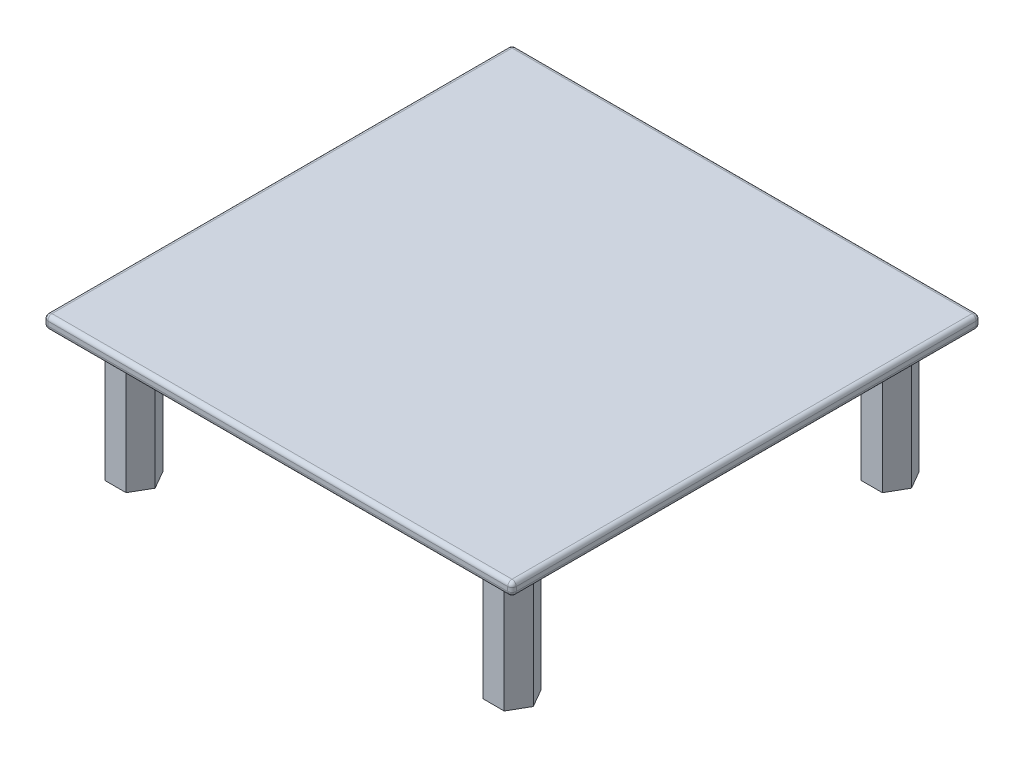
SolidWorks part; units mm, degrees
material "6061-T6 (SS)"
ref_plane "Front Plane" through (0, 0, 0) normal (0, 0, 1) x (1, 0, 0)
ref_plane "Top Plane" through (0, 0, 0) normal (0, 1, 0) x (1, 0, 0)
ref_plane "Right Plane" through (0, 0, 0) normal (1, 0, 0) x (0, 0, -1)
sketch "Sketch1" plane through (0, 0, 0) normal (0, 1, 0) x (1, 0, 0)
  line L1 (55, -55) -> (-55, -55)
  line L2 (55, -55) -> (55, 55)
  line L3 (55, 55) -> (-55, 55)
  line L4 (-55, -55) -> (-55, 55)
  line L5 (55, -55) -> (-55, 55) construction
  line L6 (55, 55) -> (-55, -55) construction
  point P0 (0, 0)
  dimension "D1" = 110
  dimension "D2" = 110
extrude "Boss-Extrude1" add sketch "Sketch1" along normal blind 3
sketch "Sketch2" plane through (0, 0, 0) normal (0, -1, 0) x (1, 0, 0)
  line L0 (-55, 55) -> (55, -55) construction
  line L1 (0, 55) -> (0, -55) construction
  line L2 (-55, 55) -> (55, 55) construction
  line L3 (55, -55) -> (-55, -55) construction
  line L4 (55, 0) -> (-55, 0) construction
  line L5 (55, 55) -> (55, -55) construction
  line L6 (-55, -55) -> (-55, 55) construction
  line L7 (55, 55) -> (-55, -55) construction
  line L8 (-39.3934, 44.3934) -> (-41.8934, 48.7235)
  line L9 (-41.8934, 48.7235) -> (-46.8934, 48.7235)
  line L10 (-46.8934, 48.7235) -> (-49.3934, 44.3934)
  line L11 (-49.3934, 44.3934) -> (-46.8934, 40.0633)
  line L12 (-46.8934, 40.0633) -> (-41.8934, 40.0633)
  line L13 (-41.8934, 40.0633) -> (-39.3934, 44.3934)
  line L14 (41.8934, 40.0633) -> (39.3934, 44.3934)
  line L15 (46.8934, 40.0633) -> (41.8934, 40.0633)
  line L16 (49.3934, 44.3934) -> (46.8934, 40.0633)
  line L17 (46.8934, 48.7235) -> (49.3934, 44.3934)
  line L18 (41.8934, 48.7235) -> (46.8934, 48.7235)
  line L19 (39.3934, 44.3934) -> (41.8934, 48.7235)
  line L20 (55, -55) -> (-55, 55) construction
  line L21 (-55, -55) -> (55, 55) construction
  line L22 (39.3934, -44.3934) -> (41.8934, -48.7235)
  line L23 (41.8934, -48.7235) -> (46.8934, -48.7235)
  line L24 (46.8934, -48.7235) -> (49.3934, -44.3934)
  line L25 (49.3934, -44.3934) -> (46.8934, -40.0633)
  line L26 (46.8934, -40.0633) -> (41.8934, -40.0633)
  line L27 (41.8934, -40.0633) -> (39.3934, -44.3934)
  line L28 (-41.8934, -40.0633) -> (-39.3934, -44.3934)
  line L29 (-46.8934, -40.0633) -> (-41.8934, -40.0633)
  line L30 (-49.3934, -44.3934) -> (-46.8934, -40.0633)
  line L31 (-46.8934, -48.7235) -> (-49.3934, -44.3934)
  line L32 (-41.8934, -48.7235) -> (-46.8934, -48.7235)
  line L33 (-39.3934, -44.3934) -> (-41.8934, -48.7235)
  circle A0 centre (-44.3934, 44.3934) radius 4.3301 construction
  circle A1 centre (44.3934, 44.3934) radius 4.3301 construction
  circle A2 centre (44.3934, -44.3934) radius 4.3301 construction
  circle A3 centre (-44.3934, -44.3934) radius 4.3301 construction
  dimension "D1" = 5
  dimension "D2" = 15
extrude "Boss-Extrude2" add sketch "Sketch2" along normal blind 32 from offset 2 offset against normal yes
fillet "Fillet2" radius 1 12 edges at (0, 3, -55) (0, 0, -55) (55, 3, 0) (55, 1.5, -55) (55, 0, 0) (0, 3, 55) (55, 1.5, 55) (0, 0, 55) (-55, 1.5, -55) (-55, 3, 0) (-55, 1.5, 55) (-55, 0, 0)
